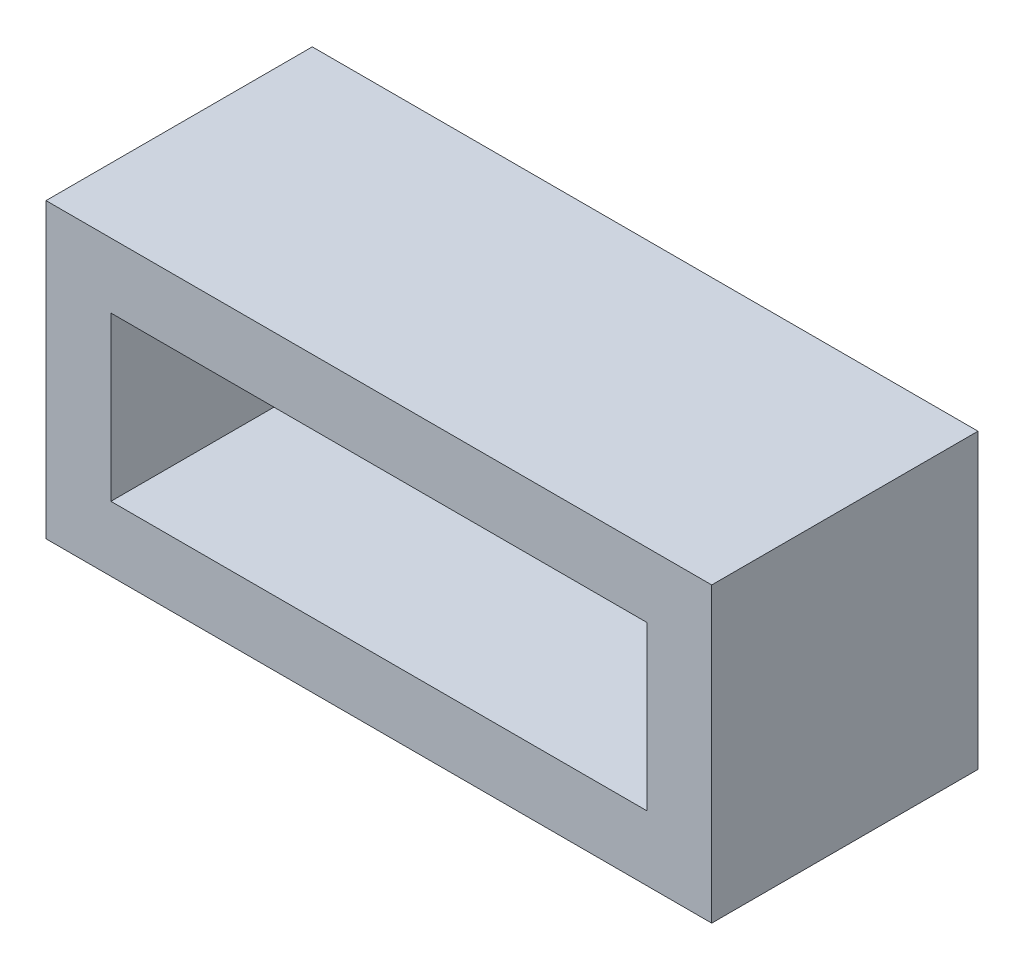
SolidWorks part; units mm, degrees
ref_plane "Front Plane" through (0, 0, 0) normal (0, 0, 1) x (1, 0, 0)
ref_plane "Top Plane" through (0, 0, 0) normal (0, 1, 0) x (1, 0, 0)
ref_plane "Right Plane" through (0, 0, 0) normal (1, 0, 0) x (0, 0, -1)
sketch "Sketch1" plane through (0, 0, 0) normal (0, 0, 1) x (1, 0, 0)
  line L1 (-10.063, -3.0625) -> (10.063, -3.0625)
  line L2 (-10.063, -3.0625) -> (-10.063, 3.0625)
  line L3 (-10.063, 3.0625) -> (10.063, 3.0625)
  line L4 (10.063, -3.0625) -> (10.063, 3.0625)
  line L5 (-10.063, -3.0625) -> (10.063, 3.0625) construction
  line L6 (-10.063, 3.0625) -> (10.063, -3.0625) construction
  line L7 (-12.5, -5.5) -> (12.5, -5.5)
  line L8 (-12.5, -5.5) -> (-12.5, 5.5)
  line L9 (-12.5, 5.5) -> (12.5, 5.5)
  line L10 (12.5, -5.5) -> (12.5, 5.5)
  line L11 (-12.5, -5.5) -> (12.5, 5.5) construction
  line L12 (-12.5, 5.5) -> (12.5, -5.5) construction
  point P0 (0, 0)
  point P6 (0, 0)
  dimension "D1" = 20.126
  dimension "D2" = 6.125
  dimension "D3" = 25
  dimension "D4" = 11
extrude "Boss-Extrude1" add sketch "Sketch1" along normal blind 10
